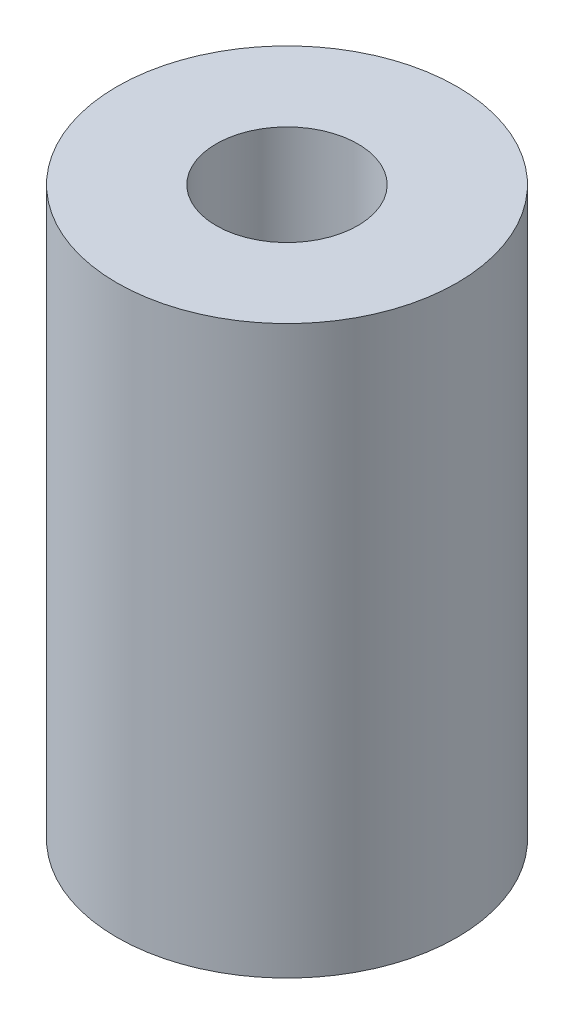
SolidWorks part; units mm, degrees
material "1060 Alloy"
ref_plane "Front" through (0, 0, 0) normal (0, 0, 1) x (1, 0, 0)
ref_plane "Top" through (0, 0, 0) normal (0, 1, 0) x (1, 0, 0)
ref_plane "Right" through (0, 0, 0) normal (1, 0, 0) x (0, 0, -1)
sketch "Sketch1" plane through (0, 0, 0) normal (0, 1, 0) x (1, 0, 0)
  circle A0 centre (0, 0) radius 6
  dimension "D1" = 12
extrude "Boss-Extrude1" add sketch "Sketch1" along normal blind 20
sketch "Sketch2" plane through (0, 20, 0) normal (0, 1, 0) x (1, 0, 0)
  circle A0 centre (0, 0) radius 2.5
  dimension "D1" = 5
extrude "Cut-Extrude1" cut sketch "Sketch2" against normal blind 10
sketch "Sketch3" plane through (0, 0, 0) normal (0, -1, 0) x (-1, 0, 0)
  circle A0 centre (0, 0) radius 2.5
  dimension "D1" = 5
extrude "Cut-Extrude2" cut sketch "Sketch3" against normal blind 10
